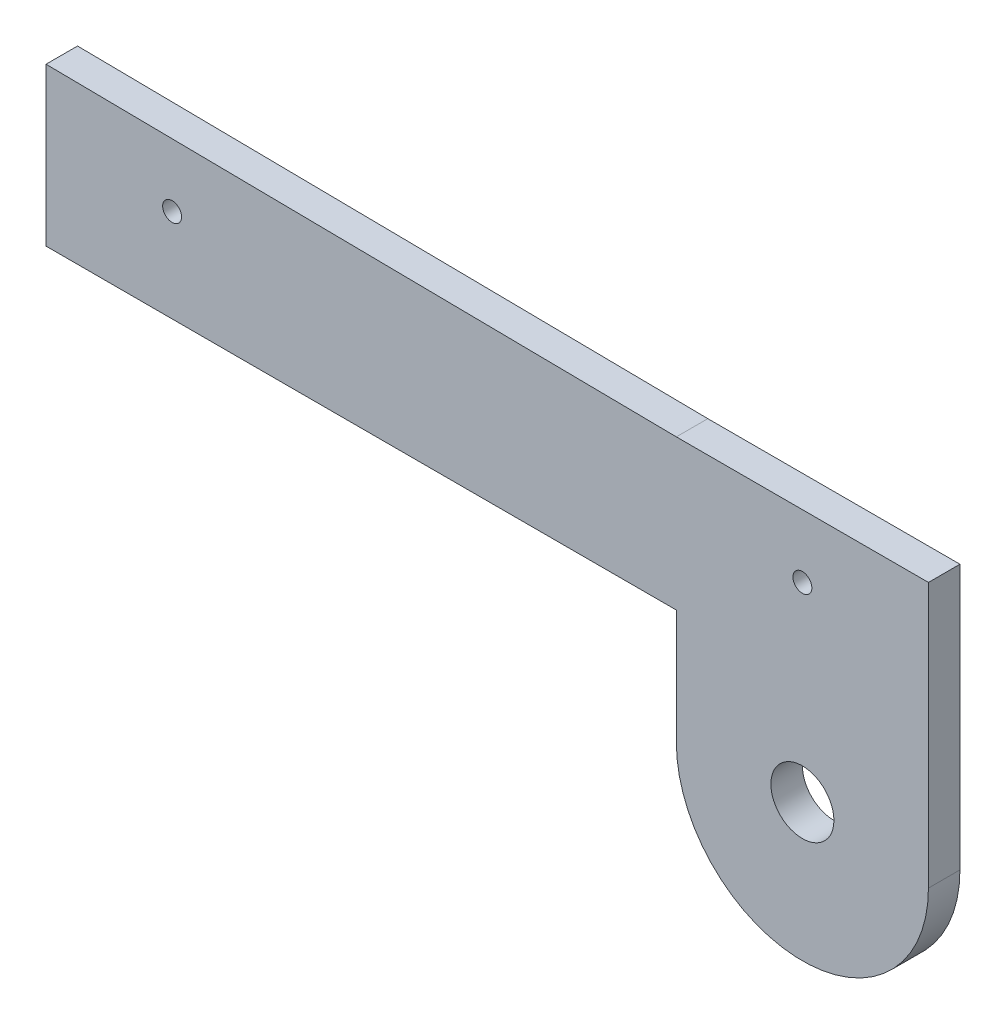
SolidWorks part; units mm, degrees
ref_plane "Front Plane" through (0, 0, 0) normal (0, 0, 1) x (1, 0, 0)
ref_plane "Top Plane" through (0, 0, 0) normal (0, 1, 0) x (1, 0, 0)
ref_plane "Right Plane" through (0, 0, 0) normal (1, 0, 0) x (0, 0, -1)
sketch "Sketch1" plane through (0, 0, 0) normal (0, 0, 1) x (1, 0, 0)
  line L0 (0, 78.0535) -> (0, -76.7078) construction
  line L1 (-108.1983, 0.6729) -> (119.7718, 0.6729) construction
  line L2 (-12.0732, -76.7078) -> (17.2347, -76.7078) construction
  line L3 (-20, -76.7078) -> (-20, -58.5041)
  line L4 (-20, -34.7078) -> (20, -34.7078)
  line L5 (20, -34.7078) -> (20, -76.7078)
  line L6 (-20, -34.7078) -> (-120, -33.5041)
  line L7 (-120, -33.5041) -> (-120, -58.5041)
  line L8 (-120, -58.5041) -> (-20, -58.5041)
  arc A0 (-20, -76.7078) -> (20, -76.7078) centre (0, -76.7078) ccw
  circle A1 centre (0, -44.7078) radius 1.5
  circle A2 centre (-100, -43.7456) radius 1.5
  dimension "D1" = 40
  dimension "D10" = 3
  dimension "D11" = 3
  dimension "D2" = 40
  dimension "D3" = 42
  dimension "D4" = 100
  dimension "D5" = 25
  dimension "D6" = 100
  dimension "D7" = 10
  dimension "D8" = 10
  dimension "D9" = 20
extrude "Boss-Extrude1" add sketch "Sketch1" along normal blind 5
sketch "Sketch2" plane through (0, 0, 5) normal (0, 0, 1) x (1, 0, 0)
  line L0 (0, -39.6329) -> (0, -110.1829) construction
  line L1 (-29.4048, -74.9079) -> (47.7155, -74.9079) construction
  circle A0 centre (0, -74.9079) radius 5
extrude "Cut-Extrude1" cut sketch "Sketch2" against normal blind 24 and the other way blind 37
